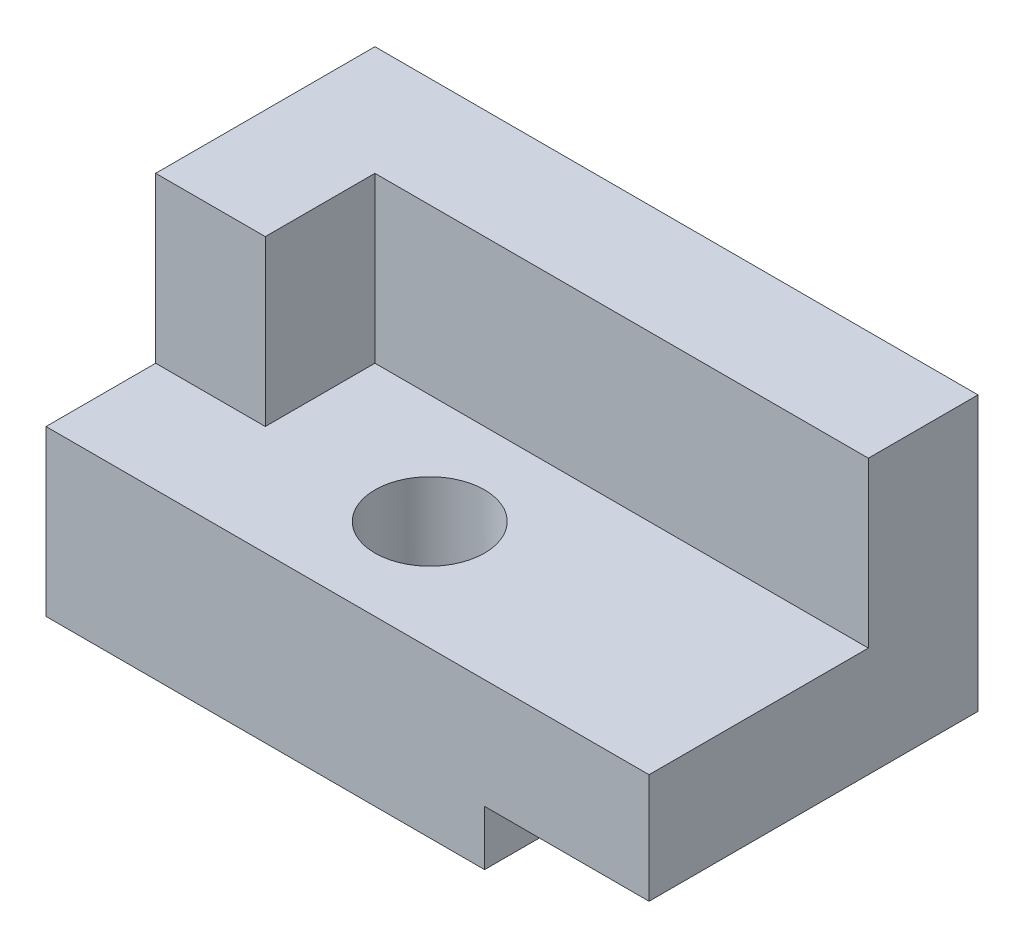
SolidWorks part; units mm, degrees
ref_plane "Front Plane" through (0, 0, 0) normal (0, 0, 1) x (1, 0, 0)
ref_plane "Top Plane" through (0, 0, 0) normal (0, 1, 0) x (1, 0, 0)
ref_plane "Right Plane" through (0, 0, 0) normal (1, 0, 0) x (0, 0, -1)
sketch "Model" plane through (0, 0, 0) normal (0, 0, 1) x (1, 0, 0)
  text T0 "No.3" font "SWTXT" height 25.4
sketch "Front Sketch" plane through (0, 0, 0) normal (0, 0, 1) x (1, 0, 0)
  line L0 (228.6, 101.6) -> (228.6, 38.1)
  line L1 (228.6, 38.1) -> (190.5, 38.1)
  line L2 (190.5, 38.1) -> (190.5, 25.4)
  line L3 (190.5, 25.4) -> (88.9, 25.4)
  line L4 (88.9, 25.4) -> (88.9, 101.6)
  line L5 (88.9, 101.6) -> (228.6, 101.6)
  line L6 (228.6, 63.5) -> (88.9, 63.5)
  line L7 (190.5, 63.5) -> (190.5, 38.1)
  line L8 (114.3, 63.5) -> (114.3, 101.6)
  line L9 (165.1, 63.5) -> (165.1, 25.4) construction
  line L10 (139.7, 63.5) -> (139.7, 25.4) construction
  line L11 (152.4, 69.85) -> (152.4, 19.05) construction
  point P17 (0, 0)
  point P18 (0, 0)
  point P19 (0, 0)
  point P20 (0, 0)
  point P21 (0, 0)
  point P22 (0, 0)
  point P23 (0, 0)
sketch "Top Sketch" plane through (0, 114.3, 0) normal (0, 1, 0) x (-1, 0, 0)
  line L0 (-228.6, 0) -> (-88.9, 0)
  line L1 (-88.9, 0) -> (-88.9, -76.2)
  line L2 (-88.9, -76.2) -> (-228.6, -76.2)
  line L3 (-228.6, -76.2) -> (-228.6, 0)
  line L4 (-114.3, -25.4) -> (-88.9, -25.4)
  line L5 (-228.6, -50.8) -> (-114.3, -50.8)
  line L6 (-114.3, -25.4) -> (-114.3, -50.8)
  line L7 (-190.5, 0) -> (-190.5, -76.2) construction
  line L8 (-152.4, -6.35) -> (-152.4, -44.45) construction
  line L9 (-133.35, -25.4) -> (-171.45, -25.4) construction
  circle A0 centre (-152.4, -25.4) radius 12.7
sketch "Right Sketch" plane through (241.3, 0, 0) normal (1, 0, 0) x (0, 0, -1)
  line L0 (38.1, 63.5) -> (0, 63.5)
  line L1 (0, 63.5) -> (0, 25.4)
  line L2 (0, 25.4) -> (76.2, 25.4)
  line L3 (76.2, 25.4) -> (76.2, 101.6)
  line L4 (76.2, 101.6) -> (50.8, 101.6)
  line L5 (50.8, 101.6) -> (50.8, 63.5)
  line L6 (50.8, 63.5) -> (25.4, 63.5)
  line L7 (25.4, 63.5) -> (25.4, 101.6)
  line L8 (25.4, 101.6) -> (50.8, 101.6)
  line L9 (25.4, 38.1) -> (76.2, 38.1)
  line L10 (12.7, 63.5) -> (12.7, 25.4) construction
  line L11 (38.1, 63.5) -> (38.1, 25.4) construction
  line L12 (25.4, 63.5) -> (25.4, 19.05) construction
  line L13 (25.4, 19.05) -> (25.4, 50.8) construction
  point P16 (0, 0)
  point P17 (0, 0)
sketch "Sketch5" plane through (0, 114.3, 0) normal (0, 1, 0) x (-1, 0, 0)
  line L0 (-88.9, -25.4) -> (-88.9, -76.2)
  line L1 (-88.9, -76.2) -> (-228.6, -76.2)
  line L2 (-228.6, -76.2) -> (-228.6, -50.8)
  line L3 (-114.3, -25.4) -> (-88.9, -25.4)
  line L4 (-228.6, -50.8) -> (-114.3, -50.8)
  line L5 (-114.3, -25.4) -> (-114.3, -50.8)
extrude "Boss-Extrude1" add sketch "Sketch5" against normal up to vertex (88.9 mm away) from vertex at -12.7 starting at point (241.3, 101.6, -76.2)
sketch "Sketch6" plane through (0, 114.3, 0) normal (0, 1, 0) x (-1, 0, 0)
  line L0 (-228.6, 0) -> (-88.9, 0)
  line L1 (-88.9, 0) -> (-88.9, -25.4)
  line L2 (-228.6, -50.8) -> (-228.6, 0)
  line L3 (-114.3, -25.4) -> (-88.9, -25.4)
  line L4 (-228.6, -50.8) -> (-114.3, -50.8)
  line L5 (-114.3, -25.4) -> (-114.3, -50.8)
extrude "Boss-Extrude2" add sketch "Sketch6" against normal up to vertex (88.9 mm away) from vertex at -50.8 starting at point (88.9, 63.5, 0)
sketch "Sketch7" plane through (0, 114.3, 0) normal (0, 1, 0) x (-1, 0, 0)
  circle A0 centre (-152.4, -25.4) radius 12.7
extrude "Cut-Extrude1" cut sketch "Sketch7" against normal through all
sketch "Sketch8" plane through (0, 0, 0) normal (0, 0, 1) x (1, 0, 0)
  line L0 (228.6, 38.1) -> (190.5, 38.1)
  line L1 (190.5, 38.1) -> (190.5, 25.4)
extrude "Cut-Extrude2" cut sketch "Sketch8" against normal through all and the other way through all
